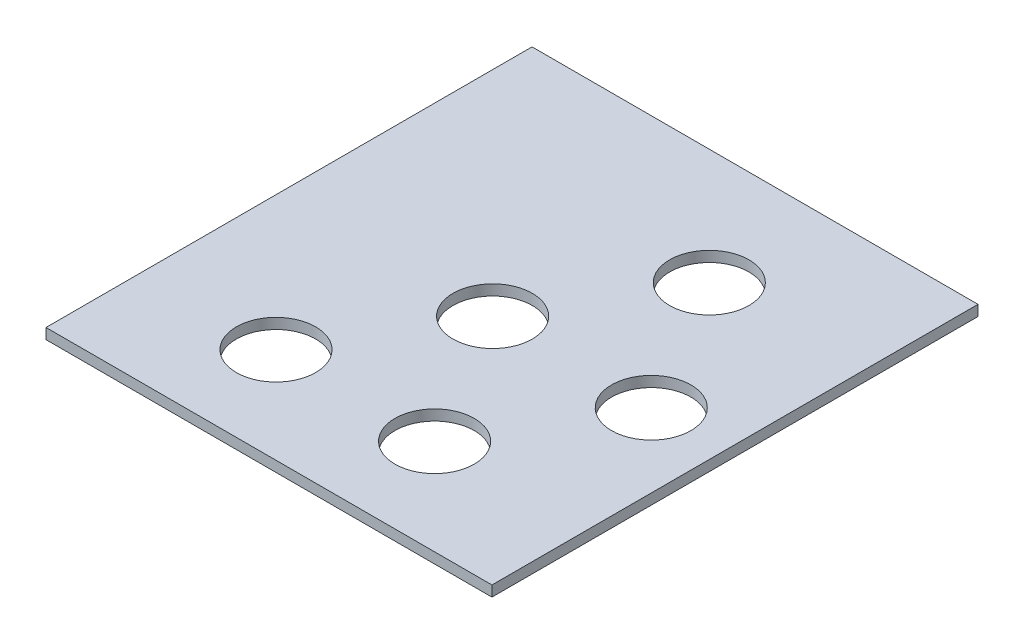
SolidWorks part; units mm, degrees
ref_plane "Front Plane" through (0, 0, 0) normal (0, 0, 1) x (1, 0, 0)
ref_plane "Top Plane" through (0, 0, 0) normal (0, 1, 0) x (1, 0, 0)
ref_plane "Right Plane" through (0, 0, 0) normal (1, 0, 0) x (0, 0, -1)
sketch "Sketch1" plane through (0, 0, 0) normal (0, 1, 0) x (1, 0, 0)
  line L0 (0, 13.8564) -> (24, 13.8564) construction
  line L1 (0, 13.8564) -> (-12, -6.9282) construction
  line L2 (-12, -6.9282) -> (12, -6.9282) construction
  line L3 (12, -6.9282) -> (0, 13.8564) construction
  line L4 (12, -6.9282) -> (24, 13.8564) construction
  line L5 (12, 6.9282) -> (12, -6.9282) construction
  line L6 (-32.315, 52.1328) -> (35.1688, 52.1328)
  line L7 (-32.315, 52.1328) -> (-32.315, -21.4172)
  line L8 (-32.315, -21.4172) -> (35.1688, -21.4172)
  line L9 (35.1688, 52.1328) -> (35.1688, -21.4172)
  line L10 (0, 0) -> (0, 13.8564) construction
  line L11 (0, 13.8564) -> (12, 34.641) construction
  line L12 (12, 34.641) -> (24, 13.8564) construction
  line L13 (12, 20.7846) -> (12, 34.641) construction
  circle A0 centre (0, 0) radius 6.9282 construction
  circle A1 centre (12, 6.9282) radius 6.9282 construction
  circle A2 centre (0, 13.8564) radius 6
  circle A3 centre (24, 13.8564) radius 6
  circle A4 centre (12, -6.9282) radius 6
  circle A5 centre (-12, -6.9282) radius 6
  circle A6 centre (12, 20.7846) radius 6.9282 construction
  circle A7 centre (12, 34.641) radius 6
  dimension "D2" = 12
  dimension "D3" = 12
  dimension "D4" = 12
  dimension "D5" = 12
  dimension "D6" = 12
  dimension "D1" = 24
extrude "Boss-Extrude1" add sketch "Sketch1" along normal blind 1.6
